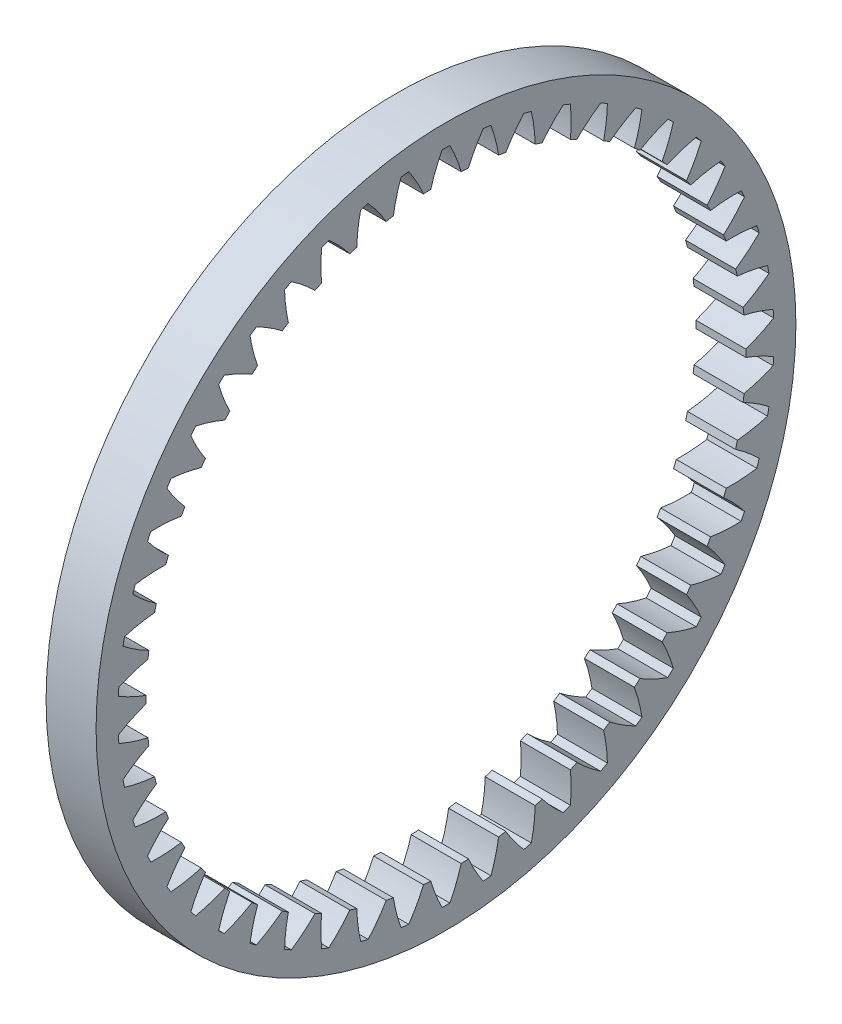
SolidWorks part; units mm, degrees
ref_plane "Plane1" through (0, 0, 0) normal (0, 0, 1) x (1, 0, 0)
ref_plane "Plane2" through (0, 0, 0) normal (0, 1, 0) x (1, 0, 0)
ref_plane "Plane3" through (0, 0, 0) normal (1, 0, 0) x (0, 0, -1)
other "Configuration Table"
sketch "HoldingSke" plane through (0, 0, 0) normal (0, 1, 0) x (1, 0, 0)
  line L0 (0, 0) -> (130.6144, -155.6602)
  line L1 (-15, 0) -> (100, 0) construction
  line L2 (0, 0) -> (-2.1039, 2.3779)
  line L3 (0, 0) -> (-11.863, 4.5341)
  line L4 (0, 0) -> (5.5511, 6.6156)
  line L5 (0, 0) -> (-23.7986, -8.8762)
  line L6 (0, 0) -> (-10.5278, -7.1032)
  line L7 (-2.1039, 2.3779) -> (3.3635, 27.1825)
  line L8 (-76.2, 54.61) -> (-54.61, 54.61)
  line L9 (-71.009, 38.7566) -> (-53.1078, 45.2721)
  line L10 (-76.2, 71.12) -> (104.1128, 71.12)
  line L11 (0, 0) -> (-12.7, 0)
  line L12 (-76.2, 101.6) -> (-76.0857, 101.6)
  line L13 (24.9733, 27.94) -> (52.9518, 28.4284)
  line L14 (24.9733, 27.94) -> (24.9746, 27.94)
  line L15 (24.9733, 27.94) -> (100.4006, 29.5858)
  circle A0 centre (0, 0) radius 88.9
  circle A1 centre (0, 0) radius 12.7
  circle A2 centre (0, 0) radius 12.7
  dimension "MHD" = 25.4
  dimension "Hub_dia" = 25.4
  dimension "Diameter" = 177.8
  dimension "Num_teeth" = 50
  dimension "Pitch" = 203.2
  dimension "Overall_len" = 25.4
  dimension "Show_teeth" = 50
  dimension "Thickness" = 12.7
  dimension "OAL" = 25.4001
  dimension "T_dim" = 21.59
  dimension "Ap" = 20
  dimension "H" = 19.05
  dimension "Pitch_radius" = 180.3128
  dimension "Width" = 12.7
  dimension "Backlash" = 0.1143
  dimension "Addendum_fac" = 1
  dimension "Dedendum_fac" = 1.25
  dimension "Clearance_fac" = 0.25
  dimension "Dedendum_add" = 0.0013
sketch "BasProSke" plane through (0, 0, 0) normal (0, 1, 0) x (1, 0, 0)
  line L0 (-10, 0) -> (60, 0) construction
  line L1 (0, 76.2) -> (0, 88.9)
  line L2 (0, 76.2) -> (12.7, 76.2)
  line L3 (12.7, 76.2) -> (12.7, 88.9)
  line L4 (12.7, 88.9) -> (0, 88.9)
  dimension "Diameter" = 177.8
  dimension "Thickness" = 12.7
  dimension "Inside_diameter" = 152.4
revolve "Base-Revolve" add sketch "BasProSke" angle 360 about L0
sketch "TooCutSke" plane through (0, 0, 0) normal (1, 0, 0) x (0, 0, -1)
  line L3 (2.779, 79.3263) -> (2.779, 53.6633) construction
  line L4 (0, 0) -> (0, 59.563) construction
  line L5 (0, 0) -> (-4.2903, 68.1927) construction
  line L6 (-34.2733, 65.1057) -> (33.553, 69.373) construction
  circle A0 centre (0, 0) radius 79.375 construction
  circle A1 centre (0, 0) radius 83.345 construction
  circle A2 centre (0, 0) radius 67.1293 construction
  circle A3 centre (0, 0) radius 76.1746 construction
  arc A4 (3.8678, 76.0763) -> (0.9777, 83.3393) centre (-34.2733, 65.1057) ccw
  arc A5 (3.8678, 76.0763) -> (-3.8678, 76.0763) centre (0, 0) ccw
  arc A6 (0.9777, 83.3393) -> (-0.9777, 83.3393) centre (0, 0) ccw
  arc A7 (-0.9777, 83.3393) -> (-3.8678, 76.0763) centre (34.2733, 65.1057) ccw
  dimension "Pitch_dia" = 158.75
  dimension "Base_dia" = 134.2586
  dimension "Root_dia" = 166.69
  dimension "Overcut_dia" = 152.3492
  dimension "Flank_rad" = 39.6875
  dimension "Half_ang" = 3.6
  dimension "Half_CT" = 2.779
extrude "ToothCut" cut sketch "TooCutSke" along normal through all
fillet "Breaks" [suppressed] radius 0.3175
fillet "RootFillets" [suppressed] radius 0.795
pattern_circular "TeethCuts" count 50 every 7.2 about axis through (-10, 0, 0) along (1, 0, 0) of "RootFillets", "Breaks", "ToothCut"
equation "' \"Pitch@HoldingSke\" = 4"
equation "' \"Num_teeth@HoldingSke\" = 24"
equation "' \"Ap@HoldingSke\" =  14.5"
equation "' \"Ap@HoldingSke\" = 14.5"
equation "' \"Width@HoldingSke\" = 0.5"
equation "' \"Diameter@HoldingSke\" = 8"
equation "' \"Show_teeth@HoldingSke\" = 100"
equation "' \"Backlash@HoldingSke\" = 0.009"
equation "' \"Addendum_fac@HoldingSke\" = 1.0"
equation "' \"Dedendum_fac@HoldingSke\" = 1.25"
equation "' \"Dedendum_add@HoldingSke\" = 0.00005"
equation "' \"Clearance_fac@HoldingSke\" = 0.25"
equation "\"Overcut_dia@TooCutSke\" = (\"Num_teeth@HoldingSke\" - 2 * \"Addendum_fac@HoldingSke\") / \"Pitch@HoldingSke\" - 0.002"
equation "\"Pitch_dia@TooCutSke\" = \"Num_teeth@HoldingSke\" / \"Pitch@HoldingSke\""
equation "\"Base_dia@TooCutSke\" = \"Num_teeth@HoldingSke\" / \"Pitch@HoldingSke\" * cos((\"Ap@HoldingSke\"  * 3.14159265 / 180)) * 0.90"
equation "\"Root_dia@TooCutSke\" = \"Num_teeth@HoldingSke\"  / \"Pitch@HoldingSke\" + 2 *  \"Dedendum_fac@HoldingSke\"/ \"Pitch@HoldingSke\" + \"Dedendum_add@HoldingSke\" * 2"
equation "\"Half_ang@TooCutSke\" = 180 / \"Num_teeth@HoldingSke\""
equation "\"Half_CT@TooCutSke\" = \"Num_teeth@HoldingSke\" / \"Pitch@HoldingSke\" * sin((3.14159265 / 2 / \"Num_teeth@HoldingSke\")) / 2 + 10 * \"Backlash@HoldingSke\" / 4"
equation "\"Flank_rad@TooCutSke\" = \"Num_teeth@HoldingSke\" / \"Pitch@HoldingSke\" / 4"
equation "\"Radius@RootFillets\"= \"Clearance_fac@HoldingSke\" / \"Pitch@HoldingSke\" + \"Dedendum_add@HoldingSke\""
equation "\"Break_rad@Breaks\" = 0.02 / \"Pitch@HoldingSke\" * 5"
equation "\"Num_teeth@TeethCuts\" = int( \"Show_teeth@HoldingSke\" ) + 1"
equation "\"Num_teeth@TeethCuts\" = ((sgn( \"Num_teeth@TeethCuts\" - \"Num_teeth@HoldingSke\" )-1)*( \"Num_teeth@TeethCuts\" - \"Num_teeth@HoldingSke\" ))/-2+ \"Num_teeth@HoldingSke\""
equation "\"Num_teeth@TeethCuts\" = ((sgn( \"Num_teeth@TeethCuts\" - 2.0)+1)*( \"Num_teeth@TeethCuts\" - 2.0))/2 +2.0"
equation "\"Angle@TeethCuts\" = 360.0 / \"Num_teeth@HoldingSke\""
equation "\"Diameter@BasProSke\" = \"Num_teeth@HoldingSke\"  / \"Pitch@HoldingSke\" + 2 *  \"Dedendum_fac@HoldingSke\"/ \"Pitch@HoldingSke\" + \"Dedendum_add@HoldingSke\" * 2 + 0.002"
equation "\"Diameter@BasProSke\" = ((sgn( \"Diameter@BasProSke\"  - \"Diameter@HoldingSke\" )+1)*( \"Diameter@BasProSke\"  - \"Diameter@HoldingSke\" ))/2 + \"Diameter@HoldingSke\""
equation "\"Inside_diameter@BasProSke\" =  (\"Num_teeth@HoldingSke\" - 2 * \"Addendum_fac@HoldingSke\") / \"Pitch@HoldingSke\" "
equation "\"Thickness@BasProSke\"  = \"Width@HoldingSke\""
